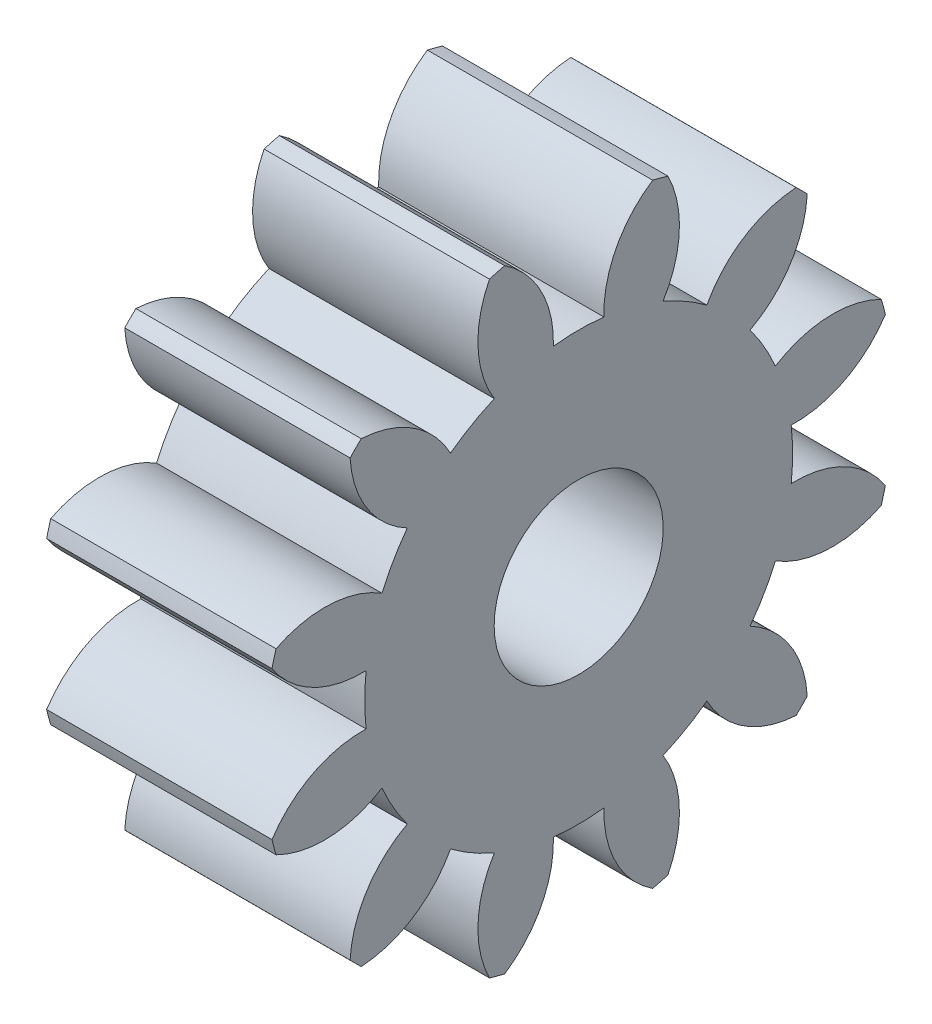
SolidWorks part; units mm, degrees
ref_plane "Plane1" through (0, 0, 0) normal (0, 0, 1) x (1, 0, 0)
ref_plane "Plane2" through (0, 0, 0) normal (0, 1, 0) x (1, 0, 0)
ref_plane "Plane3" through (0, 0, 0) normal (1, 0, 0) x (0, 0, -1)
sketch "HoldingSke" plane through (0, 0, 0) normal (0, 1, 0) x (1, 0, 0)
  line L0 (0, 0) -> (1.2227, -0.2599)
  line L1 (-15, 0) -> (100, 0) construction
  line L2 (0, 0) -> (-2.1039, 2.3779)
  line L3 (0, 0) -> (-11.863, 4.5341)
  line L4 (0, 0) -> (8.4473, 1.7955)
  line L5 (0, 0) -> (-46.8476, -17.4728)
  line L6 (0, 0) -> (-3.3159, -2.2372)
  line L7 (-2.1039, 2.3779) -> (8.6586, 51.2059)
  line L8 (-76.2, 54.61) -> (-75.7, 54.61)
  line L9 (-71.009, 38.7566) -> (-53.1078, 45.2721)
  line L10 (-76.2, 71.12) -> (104.1128, 71.12)
  line L11 (0, 0) -> (-4, 0)
  line L12 (-76.2, 101.6) -> (-76.17, 101.6)
  line L13 (24.9733, 27.94) -> (52.9518, 28.4284)
  line L14 (24.9733, 27.94) -> (24.9743, 27.94)
  line L15 (24.9733, 27.94) -> (100.4006, 29.5858)
  line L16 (-63.627, -0.8) -> (-12.827, -0.8)
  circle A0 centre (0, 0) radius 1.5
  circle A1 centre (0, 0) radius 3.799
  circle A2 centre (0, 0) radius 37.5
  circle A3 centre (0, 0) radius 1.5
  dimension "MHD" = 7.598
  dimension "Hub_dia" = 75
  dimension "Bore" = 3
  dimension "MBD" = 3
  dimension "Num_teeth" = 12
  dimension "Pitch" = 1.25
  dimension "Overall_len" = 50
  dimension "Show_teeth" = 12
  dimension "Thickness" = 4
  dimension "OAL" = 50.0001
  dimension "T_dim" = 0.5
  dimension "Ap" = 20
  dimension "H" = 19.05
  dimension "Pitch_radius" = 180.3128
  dimension "Width" = 4
  dimension "Backlash" = 0.03
  dimension "Addendum_fac" = 1
  dimension "Dedendum_fac" = 1.25
  dimension "Clearance_fac" = 0.25
  dimension "Dedendum_add" = 0.001
  dimension "Module" = 0.8
sketch "BasProSke" plane through (0, 0, 0) normal (0, 1, 0) x (1, 0, 0)
  line L0 (-10, 0) -> (60, 0) construction
  line L1 (0, 0) -> (0, 5.6)
  line L2 (0, 0) -> (4, 0)
  line L3 (4, 0) -> (4, 5.6)
  line L4 (4, 5.6) -> (0, 5.6)
  dimension "Thickness" = 4
  dimension "Diameter" = 11.2
revolve "Base-Revolve" add sketch "BasProSke" angle 360 about L0
sketch "TooCutSke" plane through (0, 0, 0) normal (1, 0, 0) x (0, 0, -1)
  line L1 (0, 0) -> (0, 107) construction
  line L2 (0, 0) -> (-0.6789, 4.7517) construction
  line L3 (0, 0) -> (-2.4668, 9.2063) construction
  line L4 (-0.6789, 4.7517) -> (-1.2334, 4.6032) construction
  arc A0 (0.4492, 3.7723) -> (-0.4492, 3.7723) centre (0, 0) ccw
  arc A1 (1.3434, 5.4626) -> (-1.3434, 5.4626) centre (0, 0) ccw
  circle A2 centre (0, 0) radius 4.8 construction
  circle A3 centre (0, 0) radius 4.5105 construction
  arc A4 (-0.4492, 3.7723) -> (-1.3434, 5.4626) centre (-2.3681, 3.8389) ccw
  arc A5 (1.3434, 5.4626) -> (0.4492, 3.7723) centre (2.3681, 3.8389) ccw
  dimension "Root_dia" = 7.598
  dimension "Overcut_dia" = 11.2508
  dimension "Pitch_dia" = 9.6
  dimension "Base_dia" = 9.021
  dimension "Flank_rad" = 1.92
  dimension "Half_ang" = 15
  dimension "Half_CT" = 0.574
extrude "ToothCut" cut sketch "TooCutSke" along normal through all
fillet "Breaks" [suppressed] radius 0.016
fillet "RootFillets" [suppressed] radius 0.201
pattern_circular "TeethCuts" count 12 every 30 about axis through (-10, 0, 0) along (1, 0, 0) of "ToothCut", "RootFillets", "Breaks"
sketch "HubNeaOneSke" plane through (0, 0, 0) normal (-1, 0, 0) x (0, 0, 1)
  circle A0 centre (0, 0) radius 3.799
  dimension "Diameter" = 7.598
extrude "HubNearOne" [suppressed] add sketch "HubNeaOneSke" along normal blind 46.0001
sketch "HubNeaBotSke" plane through (0, 0, 0) normal (-1, 0, 0) x (0, 0, 1)
  circle A0 centre (0, 0) radius 3.799
  dimension "Diameter" = 7.598
extrude "HubNearBoth" [suppressed] add sketch "HubNeaBotSke" along normal blind 23
ref_plane "FarPln" through (4, 0, 0) normal (1, 0, 0) x (0, 0, -1)
sketch "HubFarSke" plane through (4, 0, 0) normal (1, 0, 0) x (0, 0, -1)
  circle A0 centre (0, 0) radius 3.799
  dimension "Diameter" = 7.598
extrude "HubFar" [suppressed] add sketch "HubFarSke" along normal blind 23
sketch "BorSke" plane through (0, 0, 0) normal (1, 0, 0) x (0, 0, -1)
  circle A0 centre (0, 0) radius 1.5
  dimension "Diameter" = 3
extrude "Bore" cut sketch "BorSke" along normal mid plane 100.0001
sketch "KeySke" plane through (0, 0, 0) normal (1, 0, 0) x (0, 0, -1)
  line L0 (-0.6, 0) -> (-0.6, 2)
  line L1 (-0.6, 2) -> (0.6, 2)
  line L2 (0.6, 2) -> (0.6, 0)
  line L3 (0, 0) -> (0, 34) construction
  line L4 (-0.6, 0) -> (0.6, 0)
  dimension "Offset" = 2
  dimension "Width" = 1.2
extrude "Keyway" [suppressed] cut sketch "KeySke" along normal mid plane 100.0001
pattern_circular "Keyway2" [suppressed] count 2 every 90 about axis through (-10, 0, 0) along (1, 0, 0)
equation "' \"Module@HoldingSke\" = 6.35"
equation "' \"Num_teeth@HoldingSke\" = 12"
equation "' \"Ap@HoldingSke\" =  20"
equation "' \"Ap@HoldingSke\" = 20"
equation "' \"Width@HoldingSke\" = 0.5 * 25.4"
equation "' \"Hub_dia@HoldingSke\"= 1 * 25.4"
equation "' \"Hub_dia@HoldingSke\" = 1 * 25.4"
equation "' \"Overall_len@HoldingSke\" = 1.0 * 25.4"
equation "' \"Bore@HoldingSke\" = 0.75 * 25.4"
equation "' \"T_dim@HoldingSke\" = 0.1 * 25.4"
equation "' \"Width@KeySke\" = 0.25 * 25.4"
equation "' \"Show_teeth@HoldingSke\" = 13"
equation "' \"Backlash@HoldingSke\" = 0.009 * 25.4"
equation "' \"Addendum_fac@HoldingSke\" = 1.0"
equation "' \"Dedendum_fac@HoldingSke\" = 1.25"
equation "' \"Dedendum_add@HoldingSke\" = 0.00005 * 25.4"
equation "' \"Clearance_fac@HoldingSke\" = 0.25"
equation "\"Pitch@HoldingSke\" = 1 / \"Module@HoldingSke\""
equation "\"Overcut_dia@TooCutSke\" = (\"Num_teeth@HoldingSke\" + 2 * \"Addendum_fac@HoldingSke\") / \"Pitch@HoldingSke\" + 0.002 * 25.4"
equation "\"Pitch_dia@TooCutSke\" = \"Num_teeth@HoldingSke\" / \"Pitch@HoldingSke\""
equation "\"Base_dia@TooCutSke\" = \"Num_teeth@HoldingSke\" / \"Pitch@HoldingSke\" * cos((\"Ap@HoldingSke\"  * 3.14159265 / 180))"
equation "\"Root_dia@TooCutSke\" = (\"Num_teeth@HoldingSke\" + 2) / \"Pitch@HoldingSke\" - 2 * (\"Addendum_fac@HoldingSke\" + \"Dedendum_fac@HoldingSke\") / \"Pitch@HoldingSke\" - \"Dedendum_add@HoldingSke\" * 2"
equation "\"Half_ang@TooCutSke\" = 180 / \"Num_teeth@HoldingSke\""
equation "\"Half_CT@TooCutSke\" = \"Num_teeth@HoldingSke\" / \"Pitch@HoldingSke\" * sin((3.14159265 / 2 / \"Num_teeth@HoldingSke\")) / 2 - 7 * \"Backlash@HoldingSke\" / 4"
equation "\"Flank_rad@TooCutSke\" = \"Num_teeth@HoldingSke\" / \"Pitch@HoldingSke\" / 5"
equation "\"Radius@RootFillets\" = \"Clearance_fac@HoldingSke\" / \"Pitch@HoldingSke\" + \"Dedendum_add@HoldingSke\""
equation "\"Break_rad@Breaks\" = 0.02 / \"Pitch@HoldingSke\""
equation "\"Thickness@HoldingSke\" = \"Width@HoldingSke\""
equation "\"OAL@HoldingSke\" = \"Thickness@HoldingSke\""
equation "\"MHD@HoldingSke\" = (\"Num_teeth@HoldingSke\" + 2) / \"Pitch@HoldingSke\" - 2 * (\"Addendum_fac@HoldingSke\" + \"Dedendum_fac@HoldingSke\")  / \"Pitch@HoldingSke\" - \"Dedendum_add@HoldingSke\" * 2"
equation "\"MBD@HoldingSke\" = (\"Num_teeth@HoldingSke\" + 2) / \"Pitch@HoldingSke\" - 2 * (\"Addendum_fac@HoldingSke\" + \"Dedendum_fac@HoldingSke\")  / \"Pitch@HoldingSke\" - \"Dedendum_add@HoldingSke\" * 2 - 0.002 * 25.4"
equation "\"MHD@HoldingSke\" = ((sgn( \"MHD@HoldingSke\" - \"Hub_dia@HoldingSke\" )-1)*( \"MHD@HoldingSke\" - \"Hub_dia@HoldingSke\" ))/-2+ \"Hub_dia@HoldingSke\""
equation "\"MBD@HoldingSke\" = ((sgn( \"MBD@HoldingSke\" - \"Bore@HoldingSke\" )-1)*( \"MBD@HoldingSke\" - \"Bore@HoldingSke\" ))/-2+ \"Bore@HoldingSke\""
equation "\"OAL@HoldingSke\" = ((sgn( \"OAL@HoldingSke\" - \"Overall_len@HoldingSke\" )+1)*( \"OAL@HoldingSke\" - \"Overall_len@HoldingSke\" ))/2 + \"Overall_len@HoldingSke\" + 0.000002 * 25.4"
equation "\"Num_teeth@TeethCuts\" = int( \"Show_teeth@HoldingSke\" ) + 1"
equation "\"Num_teeth@TeethCuts\" = ((sgn( \"Num_teeth@TeethCuts\" - \"Num_teeth@HoldingSke\" )-1)*( \"Num_teeth@TeethCuts\" - \"Num_teeth@HoldingSke\" ))/-2+ \"Num_teeth@HoldingSke\""
equation "\"Num_teeth@TeethCuts\" = ((sgn( \"Num_teeth@TeethCuts\" - 2.0)+1)*( \"Num_teeth@TeethCuts\" - 2.0))/2 +2.0"
equation "\"Angle@TeethCuts\" = 360.0 / \"Num_teeth@HoldingSke\""
equation "\"Diameter@BasProSke\" = (\"Num_teeth@HoldingSke\" + 2 * \"Addendum_fac@HoldingSke\") / \"Pitch@HoldingSke\""
equation "\"Thickness@BasProSke\"  = \"Thickness@HoldingSke\""
equation "' \"Fillet_rad@BasProSke\" =  \"Thickness@HoldingSke\" * 0.05"
equation "' \"Fillet_rad@BasProSke\" = \"Thickness@HoldingSke\" * 0.05"
equation "\"MHD@HoldingSke\" = ((sgn( \"MHD@HoldingSke\" - \"Root_dia@TooCutSke\" )-1)*( \"MHD@HoldingSke\" - \"Root_dia@TooCutSke\" ))/-2+ \"Root_dia@TooCutSke\""
equation "\"Diameter@HubNeaOneSke\" = \"MHD@HoldingSke\""
equation "\"Length@HubNearOne\" = \"OAL@HoldingSke\" - \"Thickness@BasProSke\""
equation "\"Diameter@HubNeaBotSke\" = \"MHD@HoldingSke\""
equation "\"Length@HubNearBoth\" = ( \"OAL@HoldingSke\" - \"Thickness@BasProSke\" ) / 2.0"
equation "\"Thickness@FarPln\" = \"Thickness@BasProSke\""
equation "\"Diameter@HubFarSke\" = \"MHD@HoldingSke\""
equation "\"Length@HubFar\" = ( \"OAL@HoldingSke\" - \"Thickness@BasProSke\" ) / 2.0"
equation "\"Diameter@BorSke\" = \"MBD@HoldingSke\""
equation "\"D1@Bore\" = \"OAL@HoldingSke\" * 2.0"
equation "\"D1@Keyway\" = \"OAL@HoldingSke\" * 2.0"
equation "\"Offset@KeySke\" = \"T_dim@HoldingSke\" + \"MBD@HoldingSke\" / 2.0"
